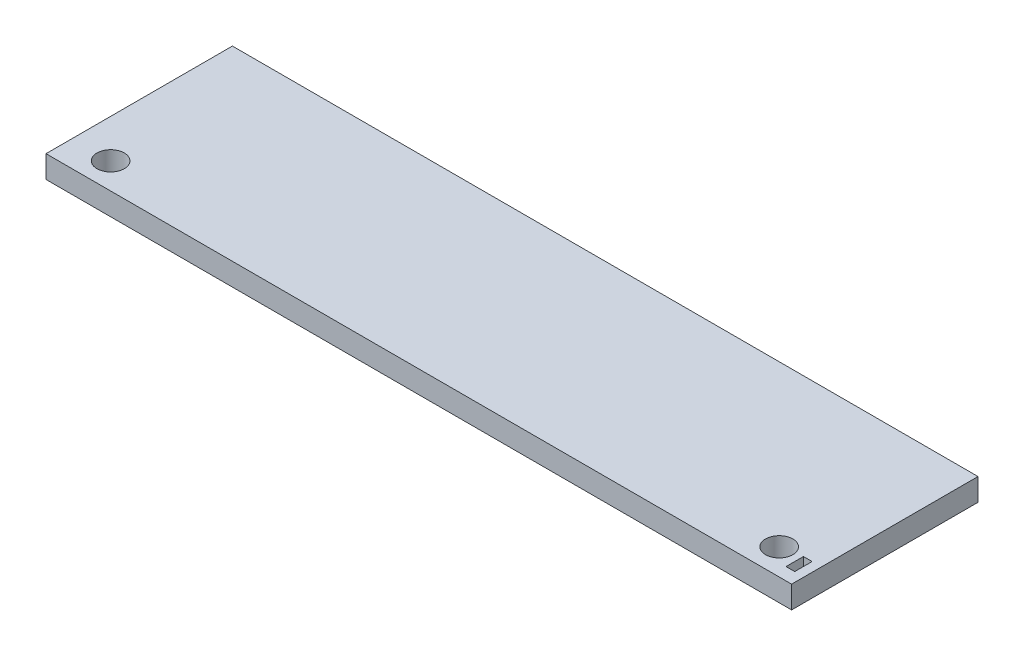
SolidWorks part; units mm, degrees
ref_plane "Plan de face" through (0, 0, 0) normal (0, 0, 1) x (1, 0, 0)
ref_plane "Plan de dessus" through (0, 0, 0) normal (0, 1, 0) x (1, 0, 0)
ref_plane "Plan de droite" through (0, 0, 0) normal (1, 0, 0) x (0, 0, -1)
sketch "Esquisse1" plane through (0, 0, 0) normal (0, 1, 0) x (1, 0, 0)
  line L1 (-300, 75) -> (300, 75)
  line L2 (-300, 75) -> (-300, -75)
  line L3 (-300, -75) -> (300, -75)
  line L4 (300, 75) -> (300, -75)
  line L5 (-300, 75) -> (300, -75) construction
  line L6 (-300, -75) -> (300, 75) construction
  point P0 (0, 0)
  dimension "D1" = 600
  dimension "D2" = 150
extrude "Boss.-Extru.1" add sketch "Esquisse1" along normal blind 18
sketch "Esquisse2" plane through (0, 18, 0) normal (0, 1, 0) x (1, 0, 0)
  line L0 (-300, 75) -> (-300, -75) construction
  line L1 (-300, 55) -> (300, 55)
  line L2 (-300, 55) -> (-300, 35)
  line L3 (-300, 35) -> (300, 35)
  line L4 (300, 55) -> (300, 35)
  line L5 (300, -75) -> (300, 75) construction
  line L6 (300, 75) -> (-300, 75) construction
  dimension "D1" = 20
  dimension "D2" = 20
sketch "Esquisse3" plane through (0, 18, 0) normal (0, 1, 0) x (1, 0, 0)
  line L0 (-238, -75) -> (-238, -33) construction
  line L1 (-300, -75) -> (300, -75) construction
  line L2 (-238, -33) -> (-300, -33) construction
  line L3 (-300, 75) -> (-300, -75) construction
  line L4 (238, -75) -> (238, -33) construction
  line L5 (238, -33) -> (300, -33) construction
  line L6 (300, -75) -> (300, 75) construction
  line L7 (238, -33) -> (300, -75) construction
  line L8 (-238, -33) -> (-300, -75) construction
  circle A0 centre (269, -54) radius 11
  circle A1 centre (-269, -54) radius 11
  dimension "D5" = 22
  dimension "D6" = 22
  dimension "D1" = 62
  dimension "D2" = 42
  dimension "D3" = 62
  dimension "D4" = 42
extrude "Enlèv. mat.-Extru.1" cut sketch "Esquisse3" against normal blind 20
sketch "Esquisse4" plane through (0, 18, 0) normal (0, 1, 0) x (1, 0, 0)
  line L0 (300, -75) -> (300, 75) construction
  line L1 (285.5, -51) -> (292.5, -51)
  line L2 (285.5, -51) -> (285.5, -65)
  line L3 (285.5, -65) -> (292.5, -65)
  line L4 (292.5, -51) -> (292.5, -65)
  line L5 (285.5, -51) -> (292.5, -65) construction
  line L6 (285.5, -65) -> (292.5, -51) construction
  line L7 (-300, -75) -> (300, -75) construction
  point P0 (289, -58)
  dimension "D1" = 14
  dimension "D2" = 7
  dimension "D3" = 7.5
  dimension "D4" = 10
extrude "Enlèv. mat.-Extru.2" cut sketch "Esquisse4" against normal blind 12
